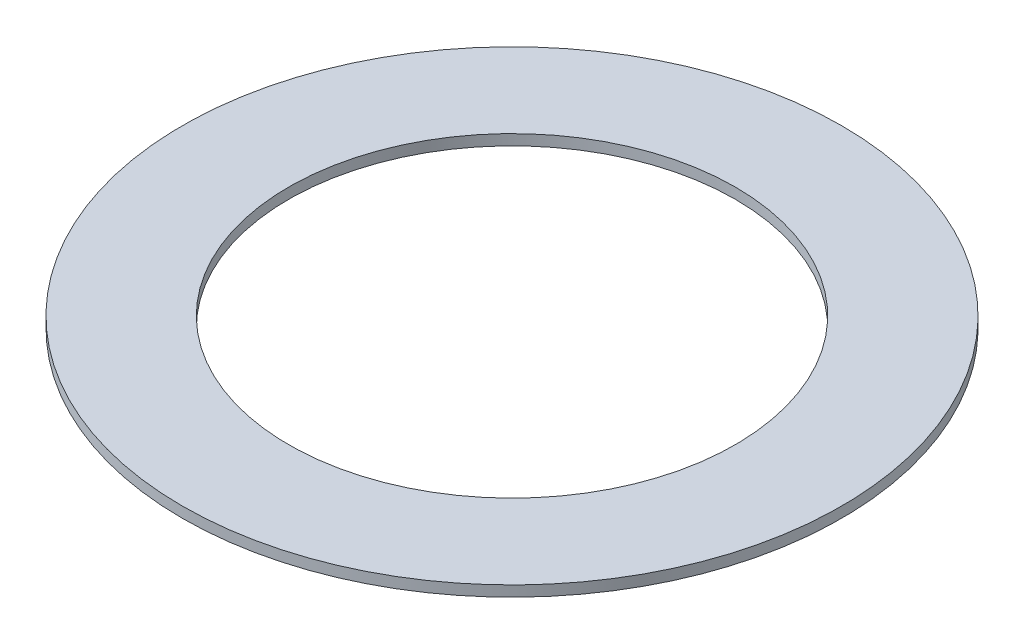
SolidWorks part; units mm, degrees
ref_plane "Front Plane" through (0, 0, 0) normal (0, 0, 1) x (1, 0, 0)
ref_plane "Top Plane" through (0, 0, 0) normal (0, 1, 0) x (1, 0, 0)
ref_plane "Right Plane" through (0, 0, 0) normal (1, 0, 0) x (0, 0, -1)
sketch "Sketch3" plane through (0, 0, 0) normal (0, 0, 1) x (1, 0, 0)
  line L0 (0, 0) -> (23231.8298, 0) construction
  line L1 (0, 0) -> (0, 23231.8298) construction
  line L2 (11, -0.5) -> (13, -0.25) construction
  line L3 (10.5, -0.25) -> (11, -0.25)
  line L4 (10.5, -0.25) -> (10.5, 0.25)
  line L5 (10.5, 0.25) -> (15.5, 0.25)
  line L6 (15.5, -0.25) -> (15.5, 0.25)
  line L7 (10.5, -0.25) -> (15.5, 0.25) construction
  line L8 (10.5, 0.25) -> (15.5, -0.25) construction
  line L9 (11, -0.5) -> (15, -0.5) construction
  line L10 (11, -0.25) -> (11, 0)
  line L11 (11, 0) -> (15, 0)
  line L12 (15, -0.25) -> (15, 0)
  line L13 (13, -0.25) -> (15, 0) construction
  line L14 (11, 0) -> (13, -0.25) construction
  line L15 (11, -0.5) -> (11, -0.25) construction
  line L16 (11, -0.25) -> (13, -0.25) construction
  line L17 (15, -0.25) -> (15.5, -0.25)
  line L18 (13, -0.25) -> (15, -0.5) construction
  line L19 (13, -0.25) -> (15, -0.25) construction
  line L20 (15, -0.5) -> (15, -0.25) construction
  point P5 (13, 0)
  point P10 (13, -0.25)
  point P19 (13, 0.25)
  dimension "D1" = 13
  dimension "D2" = 5
  dimension "D3" = 4
  dimension "D4" = 0.5
  dimension "D5" = 0.5
revolve "Revolve1" add sketch "Sketch3" angle 360 about L1
